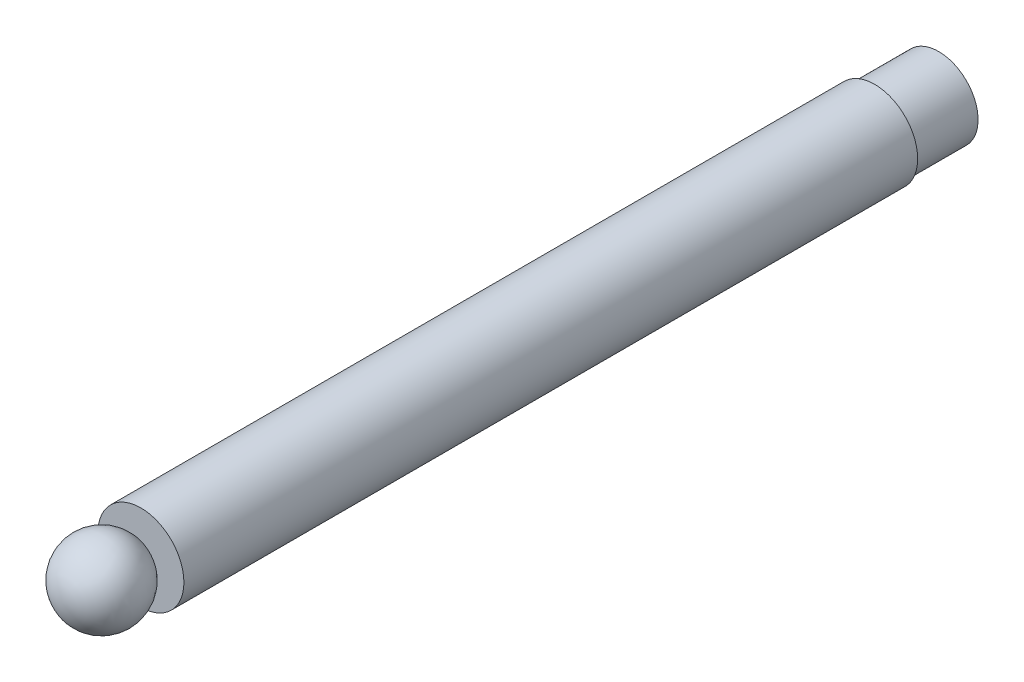
SolidWorks part; units mm, degrees
ref_plane "Front Plane" through (0, 0, 0) normal (0, 0, 1) x (1, 0, 0)
ref_plane "Top Plane" through (0, 0, 0) normal (0, 1, 0) x (1, 0, 0)
ref_plane "Right Plane" through (0, 0, 0) normal (1, 0, 0) x (0, 0, -1)
sketch "Sketch1" plane through (0, 0, 0) normal (0, 0, 1) x (1, 0, 0)
  circle A0 centre (0, 0) radius 8
  dimension "D1" = 16
extrude "Boss-Extrude1" add sketch "Sketch1" along normal blind 13
sketch "Sketch2" plane through (0, 0, 13) normal (0, 0, 1) x (1, 0, 0)
  circle A0 centre (0, 0) radius 8.7333
extrude "Boss-Extrude2" add sketch "Sketch2" along normal blind 149
ref_plane "Plane1" through (0, 0, 0) normal (0, 1, 0) x (1, 0, 0)
sketch "Sketch3" plane through (0, 0, 0) normal (0, 1, 0) x (1, 0, 0)
  line L0 (0, -162) -> (0, -178)
  line L1 (-8.7333, -162) -> (8.7333, -162) construction
  arc A0 (0, -162) -> (0, -178) centre (0, -170) cw
  dimension "D1" = 8
revolve "Revolve1" add sketch "Sketch3" angle 360 about L0
